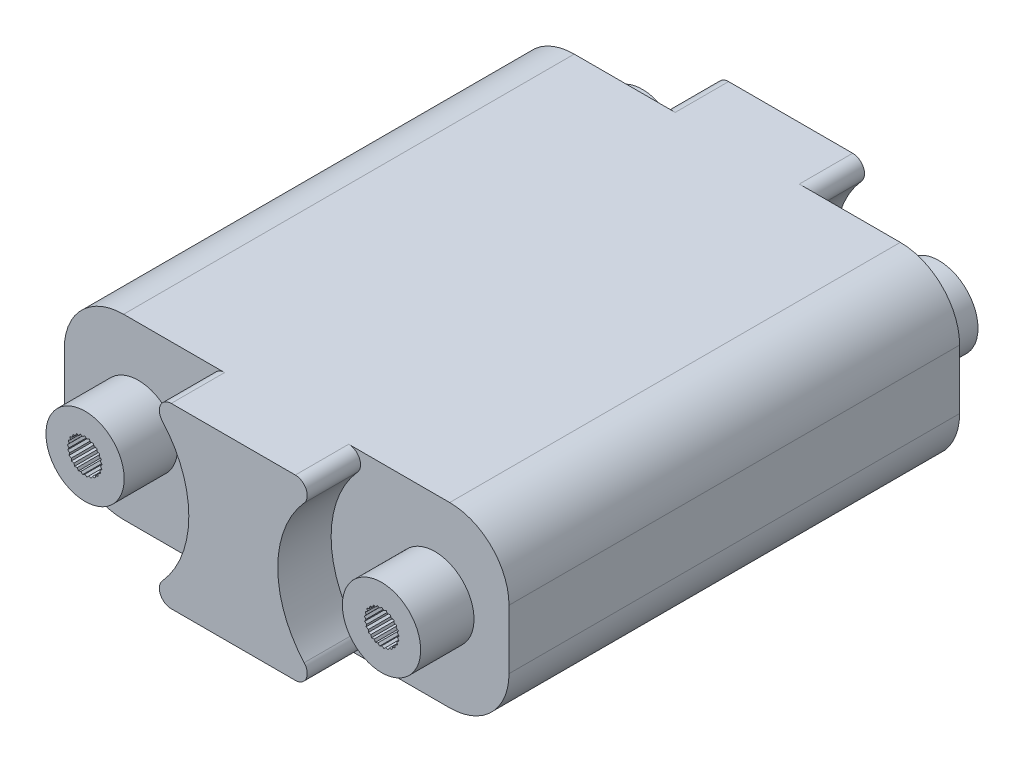
SolidWorks part; units mm, degrees
ref_plane "Спереди" through (0, 0, 0) normal (0, 0, 1) x (1, 0, 0)
ref_plane "Сверху" through (0, 0, 0) normal (0, 1, 0) x (1, 0, 0)
ref_plane "Справа" through (0, 0, 0) normal (1, 0, 0) x (0, 0, -1)
sketch "Sketch1" plane through (0, 0, 0) normal (0, 1, 0) x (1, 0, 0)
  line L1 (37.5, 47) -> (-37.5, 47)
  line L2 (37.5, 47) -> (37.5, -47)
  line L3 (37.5, -47) -> (-37.5, -47)
  line L4 (-37.5, 47) -> (-37.5, -47)
  line L5 (37.5, 47) -> (-37.5, -47) construction
  line L6 (37.5, -47) -> (-37.5, 47) construction
  point P0 (0, 0)
extrude "Boss-Extrude1" add sketch "Sketch1" along normal blind 30
sketch "Sketch2" plane through (0, 0, 47) normal (0, 0, 1) x (1, 0, 0)
  line L5 (-37.5, 0) -> (37.5, 0) construction
  line L6 (-37.5, 30) -> (-17.4742, 30)
  line L7 (-37.5, 30) -> (-37.5, 0)
  line L8 (-37.5, 0) -> (-17.4742, 0)
  line L9 (-17.4742, 30) -> (-17.4742, 0)
extrude "Cut-Extrude5" cut sketch "Sketch2" against normal blind 9
sketch "Sketch7" plane through (0, 0, -47) normal (0, 0, -1) x (-1, 0, 0)
  line L1 (37.5, 0) -> (17.4742, 0)
  line L2 (37.5, 0) -> (37.5, 30)
  line L3 (37.5, 30) -> (17.4742, 30)
  line L4 (17.4742, 0) -> (17.4742, 30)
extrude "Cut-Extrude6" cut sketch "Sketch7" against normal blind 9
sketch "Sketch8" plane through (0, 0, 38) normal (0, 0, 1) x (1, 0, 0)
  circle A0 centre (-25, 15) radius 6.6
extrude "Boss-Extrude2" add sketch "Sketch8" along normal blind 9
sketch "Sketch9" plane through (0, 0, -38) normal (0, 0, -1) x (-1, 0, 0)
  circle A0 centre (25, 15) radius 6.6
extrude "Boss-Extrude3" add sketch "Sketch9" along normal blind 9
fillet "Fillet1" radius 10 2 edges at (-37.5, 0, 0) (-37.5, 30, 0)
sketch "Sketch10" plane through (0, 0, 47) normal (0, 0, 1) x (1, 0, 0)
  line L0 (-17.4742, 0) -> (37.5, 0) construction
  line L1 (-17.4742, 30) -> (37.5, 30) construction
  line L2 (-15.9861, 30) -> (-17.4742, 30)
  line L3 (-17.4742, 30) -> (-17.4742, 0)
  line L4 (-17.4742, 0) -> (-15.9861, 0)
  arc A0 (-15.9861, 0) -> (-15.9861, 30) centre (-25, 15) ccw
extrude "Cut-Extrude7" cut sketch "Sketch10" against normal blind 9
sketch "Sketch11" plane through (0, 0, -47) normal (0, 0, -1) x (-1, 0, 0)
  line L0 (-37.5, 30) -> (17.4742, 30) construction
  line L1 (15.9861, 30) -> (17.4742, 30)
  line L2 (17.4742, 30) -> (17.4742, 0)
  line L3 (17.4742, 0) -> (15.9861, 0)
  arc A0 (15.9861, 0) -> (15.9861, 30) centre (25, 15) cw
extrude "Cut-Extrude8" cut sketch "Sketch11" against normal blind 9
fillet "Fillet2" radius 2 4 edges at (-15.9861, 30, 42.5) (-15.9861, 0, 42.5) (-15.9861, 0, -42.5) (-15.9861, 30, -42.5)
sketch "Sketch12" plane through (0, 0, 0) normal (0, 0, 1) x (1, 0, 0)
  line L0 (-25.0443, 17.9683) -> (-25.3808, 17.6972)
  line L1 (-25.0443, 17.9683) -> (-24.7078, 17.6972)
  line L2 (-25.0443, 17.9683) -> (-25.0443, 15.0333) construction
  line L3 (-24.3144, 17.8761) -> (-24.0559, 17.5298)
  line L4 (-24.3144, 17.8761) -> (-24.7078, 17.6972)
  line L5 (-23.6304, 17.6053) -> (-23.4661, 17.2055)
  line L6 (-23.6304, 17.6053) -> (-24.0559, 17.5298)
  line L7 (-23.0352, 17.1729) -> (-22.9755, 16.7448)
  line L8 (-23.0352, 17.1729) -> (-23.4661, 17.2055)
  line L9 (-22.5662, 16.606) -> (-22.6148, 16.1766)
  line L10 (-22.5662, 16.606) -> (-22.9755, 16.7448)
  line L11 (-22.2529, 15.9403) -> (-22.4069, 15.5365)
  line L12 (-22.2529, 15.9403) -> (-22.6148, 16.1766)
  line L13 (-22.1151, 15.2176) -> (-22.3646, 14.8647)
  line L14 (-22.1151, 15.2176) -> (-22.4069, 15.5365)
  line L15 (-22.1613, 14.4834) -> (-22.4907, 14.2036)
  line L16 (-22.1613, 14.4834) -> (-22.3646, 14.8647)
  line L17 (-22.3886, 13.7837) -> (-22.7773, 13.5946)
  line L18 (-22.3886, 13.7837) -> (-22.4907, 14.2036)
  line L19 (-22.7828, 13.1625) -> (-23.2063, 13.0761)
  line L20 (-22.7828, 13.1625) -> (-22.7773, 13.5946)
  line L21 (-23.3191, 12.6589) -> (-23.7508, 12.6805)
  line L22 (-23.3191, 12.6589) -> (-23.2063, 13.0761)
  line L23 (-23.9639, 12.3044) -> (-24.3766, 12.4327)
  line L24 (-23.9639, 12.3044) -> (-23.7508, 12.6805)
  line L25 (-24.6764, 12.1215) -> (-25.0443, 12.3483)
  line L26 (-24.6764, 12.1215) -> (-24.3766, 12.4327)
  line L27 (-25.4122, 12.1215) -> (-25.712, 12.4327)
  line L28 (-25.4122, 12.1215) -> (-25.0443, 12.3483)
  line L29 (-26.1247, 12.3044) -> (-26.3378, 12.6805)
  line L30 (-26.1247, 12.3044) -> (-25.712, 12.4327)
  line L31 (-26.7694, 12.6589) -> (-26.8823, 13.0761)
  line L32 (-26.7694, 12.6589) -> (-26.3378, 12.6805)
  line L33 (-27.3058, 13.1625) -> (-27.3113, 13.5946)
  line L34 (-27.3058, 13.1625) -> (-26.8823, 13.0761)
  line L35 (-27.7, 13.7837) -> (-27.5979, 14.2036)
  line L36 (-27.7, 13.7837) -> (-27.3113, 13.5946)
  line L37 (-27.9273, 14.4834) -> (-27.724, 14.8647)
  line L38 (-27.9273, 14.4834) -> (-27.5979, 14.2036)
  line L39 (-27.9735, 15.2176) -> (-27.6817, 15.5365)
  line L40 (-27.9735, 15.2176) -> (-27.724, 14.8647)
  line L41 (-27.8356, 15.9403) -> (-27.4738, 16.1766)
  line L42 (-27.8356, 15.9403) -> (-27.6817, 15.5365)
  line L43 (-27.5224, 16.606) -> (-27.1131, 16.7448)
  line L44 (-27.5224, 16.606) -> (-27.4738, 16.1766)
  line L45 (-27.0534, 17.1729) -> (-26.6225, 17.2055)
  line L46 (-27.0534, 17.1729) -> (-27.1131, 16.7448)
  line L47 (-26.4582, 17.6053) -> (-26.0327, 17.5298)
  line L48 (-26.4582, 17.6053) -> (-26.6225, 17.2055)
  line L49 (-25.7742, 17.8761) -> (-25.3808, 17.6972)
  line L50 (-25.7742, 17.8761) -> (-26.0327, 17.5298)
  circle A1 centre (-25.0443, 15.0333) radius 2.935 construction
  circle A2 centre (-25.0443, 15.0333) radius 2.685 construction
  point P57 (-25.0443, 15.0333)
sketch "Sketch13" plane through (0, 0, 47) normal (0, 0, 1) x (1, 0, 0)
  line L0 (-26.6225, 17.2055) -> (-26.4582, 17.6053)
  line L1 (-26.4582, 17.6053) -> (-26.0327, 17.5298)
  line L2 (-26.0327, 17.5298) -> (-25.7742, 17.8761)
  line L3 (-25.7742, 17.8761) -> (-25.3808, 17.6972)
  line L4 (-25.3808, 17.6972) -> (-25.0443, 17.9683)
  line L5 (-25.0443, 17.9683) -> (-24.7078, 17.6972)
  line L6 (-24.7078, 17.6972) -> (-24.3144, 17.8761)
  line L7 (-24.3144, 17.8761) -> (-24.0559, 17.5298)
  line L8 (-24.0559, 17.5298) -> (-23.6304, 17.6053)
  line L9 (-23.6304, 17.6053) -> (-23.4661, 17.2055)
  line L10 (-23.4661, 17.2055) -> (-23.0352, 17.1729)
  line L11 (-23.0352, 17.1729) -> (-22.9755, 16.7448)
  line L12 (-22.9755, 16.7448) -> (-22.5662, 16.606)
  line L13 (-22.5662, 16.606) -> (-22.6148, 16.1766)
  line L14 (-22.6148, 16.1766) -> (-22.2529, 15.9403)
  line L15 (-22.2529, 15.9403) -> (-22.4069, 15.5365)
  line L16 (-22.4069, 15.5365) -> (-22.1151, 15.2176)
  line L17 (-22.1151, 15.2176) -> (-22.3646, 14.8647)
  line L18 (-22.3646, 14.8647) -> (-22.1613, 14.4834)
  line L19 (-22.1613, 14.4834) -> (-22.4907, 14.2036)
  line L20 (-22.4907, 14.2036) -> (-22.3886, 13.7837)
  line L21 (-22.3886, 13.7837) -> (-22.7773, 13.5946)
  line L22 (-22.7773, 13.5946) -> (-22.7828, 13.1625)
  line L23 (-22.7828, 13.1625) -> (-23.2063, 13.0761)
  line L24 (-23.2063, 13.0761) -> (-23.3191, 12.6589)
  line L25 (-23.3191, 12.6589) -> (-23.7508, 12.6805)
  line L26 (-23.7508, 12.6805) -> (-23.9639, 12.3044)
  line L27 (-23.9639, 12.3044) -> (-24.3766, 12.4327)
  line L28 (-24.3766, 12.4327) -> (-24.6764, 12.1215)
  line L29 (-24.6764, 12.1215) -> (-25.0443, 12.3483)
  line L30 (-25.0443, 12.3483) -> (-25.4122, 12.1215)
  line L31 (-25.4122, 12.1215) -> (-25.712, 12.4327)
  line L32 (-25.712, 12.4327) -> (-26.1247, 12.3044)
  line L33 (-26.1247, 12.3044) -> (-26.3378, 12.6805)
  line L34 (-26.3378, 12.6805) -> (-26.7694, 12.6589)
  line L35 (-26.7694, 12.6589) -> (-26.8823, 13.0761)
  line L36 (-26.8823, 13.0761) -> (-27.3058, 13.1625)
  line L37 (-27.3058, 13.1625) -> (-27.3113, 13.5946)
  line L38 (-27.3113, 13.5946) -> (-27.7, 13.7837)
  line L39 (-27.7, 13.7837) -> (-27.5979, 14.2036)
  line L40 (-27.5979, 14.2036) -> (-27.9273, 14.4834)
  line L41 (-27.9273, 14.4834) -> (-27.724, 14.8647)
  line L42 (-27.724, 14.8647) -> (-27.9735, 15.2176)
  line L43 (-27.9735, 15.2176) -> (-27.6817, 15.5365)
  line L44 (-27.6817, 15.5365) -> (-27.8356, 15.9403)
  line L45 (-27.8356, 15.9403) -> (-27.4738, 16.1766)
  line L46 (-27.4738, 16.1766) -> (-27.5224, 16.606)
  line L47 (-27.5224, 16.606) -> (-27.1131, 16.7448)
  line L48 (-27.1131, 16.7448) -> (-27.0534, 17.1729)
  line L49 (-27.0534, 17.1729) -> (-26.6225, 17.2055)
extrude "Cut-Extrude10" cut sketch "Sketch13" against normal blind 4
sketch "Sketch14" plane through (0, 0, 47) normal (0, 0, 1) x (1, 0, 0)
  line L0 (0, 30) -> (37.5, 30)
  line L2 (0, 0) -> (0, 30)
  line L3 (-10.4656, 30) -> (37.5, 30) construction
  line L4 (37.5, 30) -> (37.5, 0)
  line L5 (37.5, 0) -> (0, 0)
extrude "Cut-Extrude11" cut sketch "Sketch14" against normal blind 94
mirror "Mirror2" about plane through (0, 0, -47) normal (-1, 0, 0) of bodies 122
